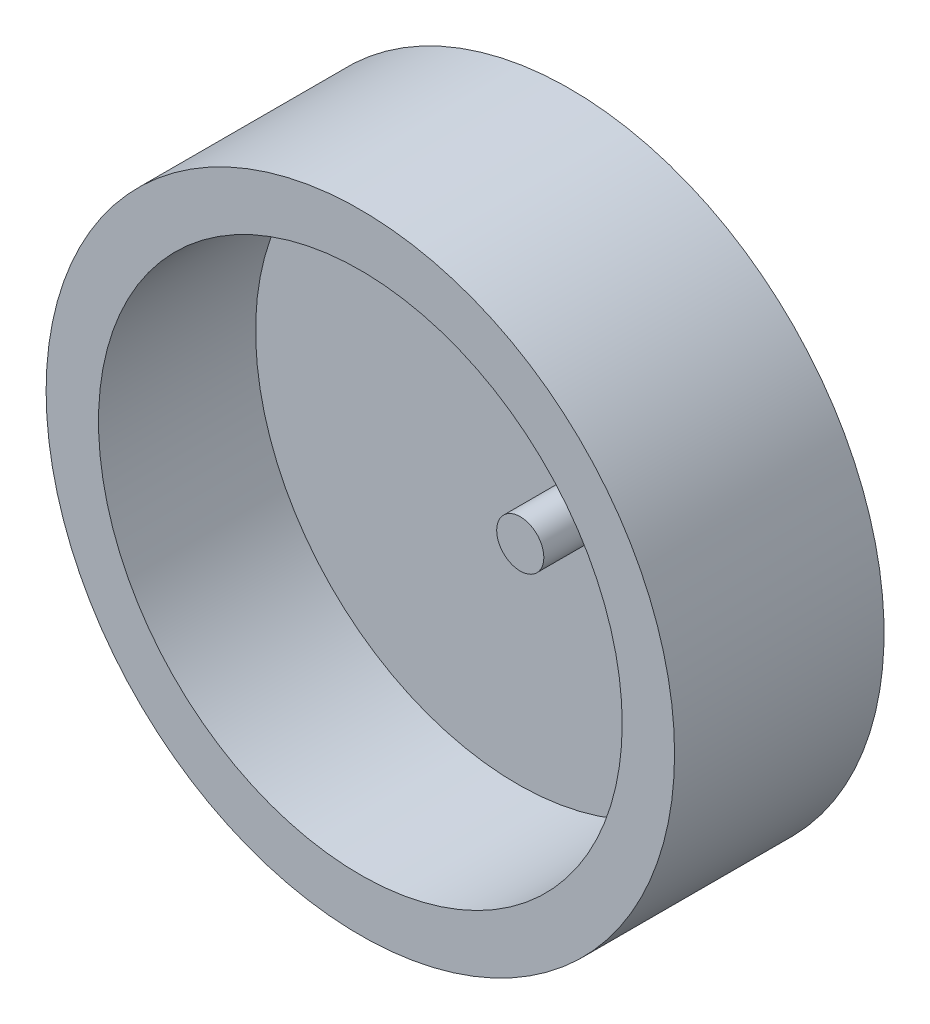
SolidWorks part; units mm, degrees
ref_plane "Front Plane" through (0, 0, 0) normal (0, 0, 1) x (1, 0, 0)
ref_plane "Top Plane" through (0, 0, 0) normal (0, 1, 0) x (1, 0, 0)
ref_plane "Right Plane" through (0, 0, 0) normal (1, 0, 0) x (0, 0, -1)
sketch "Sketch1" plane through (0, 0, 0) normal (0, 0, 1) x (1, 0, 0)
  circle A0 centre (0, 0) radius 50
  circle A1 centre (0, 0) radius 60
  dimension "D1" = 100
  dimension "D2" = 10
extrude "Boss-Extrude2" add sketch "Sketch1" along normal blind 30
sketch "Sketch2" plane through (0, 0, 0) normal (0, 0, -1) x (-1, 0, 0)
  circle A1 centre (0, 0) radius 60
  circle A2 centre (0, 0) radius 60
  dimension "D1" = 0
extrude "Boss-Extrude3" add sketch "Sketch2" along normal blind 10
sketch "Sketch3" plane through (0, 0, 0) normal (0, 0, 1) x (1, 0, 0)
  line L0 (-60, 0) -> (60, 0) construction
  circle A0 centre (0, 0) radius 60 construction
  circle A1 centre (10.5345, 0) radius 35 construction
  circle A2 centre (10.5345, 0) radius 4.5
  dimension "D1" = 70
  dimension "D3" = 9
  dimension "D2" = 10.5345
extrude "Boss-Extrude4" add sketch "Sketch3" along normal blind 10
